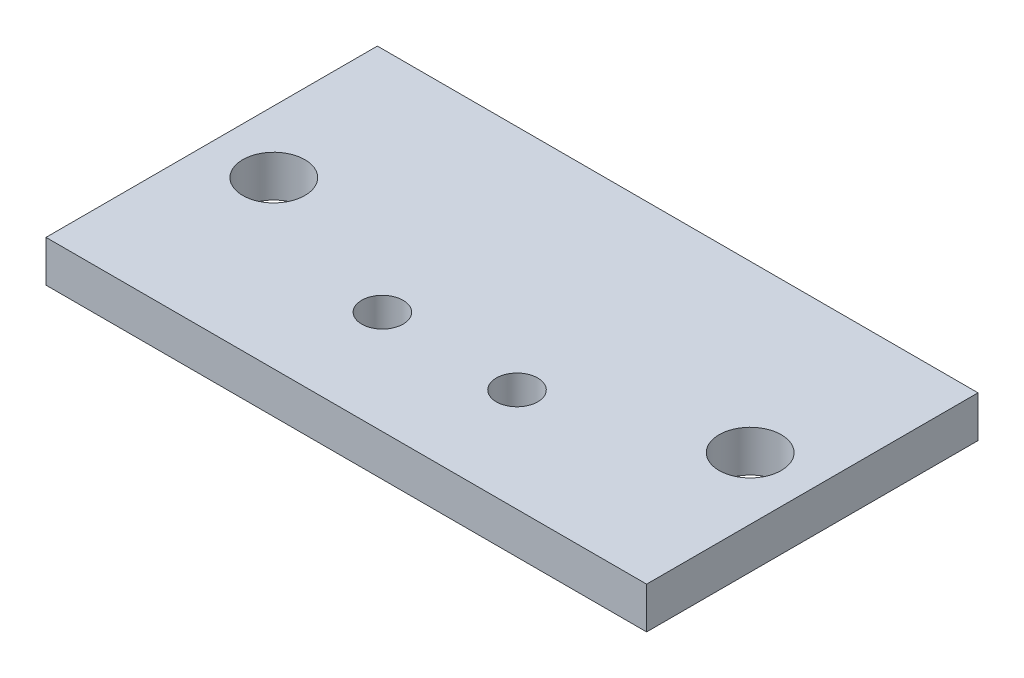
SolidWorks part; units mm, degrees
ref_plane "Alzado" through (0, 0, 0) normal (0, 0, 1) x (1, 0, 0)
ref_plane "Planta" through (0, 0, 0) normal (0, 1, 0) x (1, 0, 0)
ref_plane "Vista lateral" through (0, 0, 0) normal (1, 0, 0) x (0, 0, -1)
sketch "Croquis1" plane through (0, 0, 0) normal (0, 1, 0) x (1, 0, 0)
  line L0 (14.5, 8) -> (14.5, 0) construction
  line L2 (14.5, -8) -> (14.5, 8)
  line L3 (14.5, 8) -> (-14.5, 8)
  line L4 (-14.5, -8) -> (-14.5, 8)
  line L5 (14.5, -8) -> (-14.5, 8) construction
  line L6 (14.5, 8) -> (-14.5, -8) construction
  line L7 (14.5, 0) -> (11.5, 0) construction
  line L8 (0, 8) -> (0, -8.0077) construction
  line L10 (-6.25, -8.0077) -> (6.25, -8.0077) construction
  line L11 (-6.25, -8.0077) -> (-6.25, -1.5077) construction
  line L12 (-6.25, -1.5077) -> (6.25, -1.5077) construction
  line L13 (6.25, -1.5077) -> (6.25, -8.0077) construction
  line L14 (-6.25, -8.0077) -> (-3.25, -8.0077) construction
  line L15 (-3.25, -8.0077) -> (-3.25, -3.0077) construction
  line L16 (-14.5, -8) -> (14.5, -8)
  circle A0 centre (11.5, 0) radius 1.5
  circle A1 centre (-11.5, 0) radius 1.5
  circle A4 centre (-3.25, -3.0077) radius 1
  circle A5 centre (3.25, -3.0077) radius 1
  point P0 (0, 0)
  dimension "D3" = 3
  dimension "D1" = 29
  dimension "D2" = 16
extrude "Saliente-Extruir1" add sketch "Croquis1" along normal blind 2
